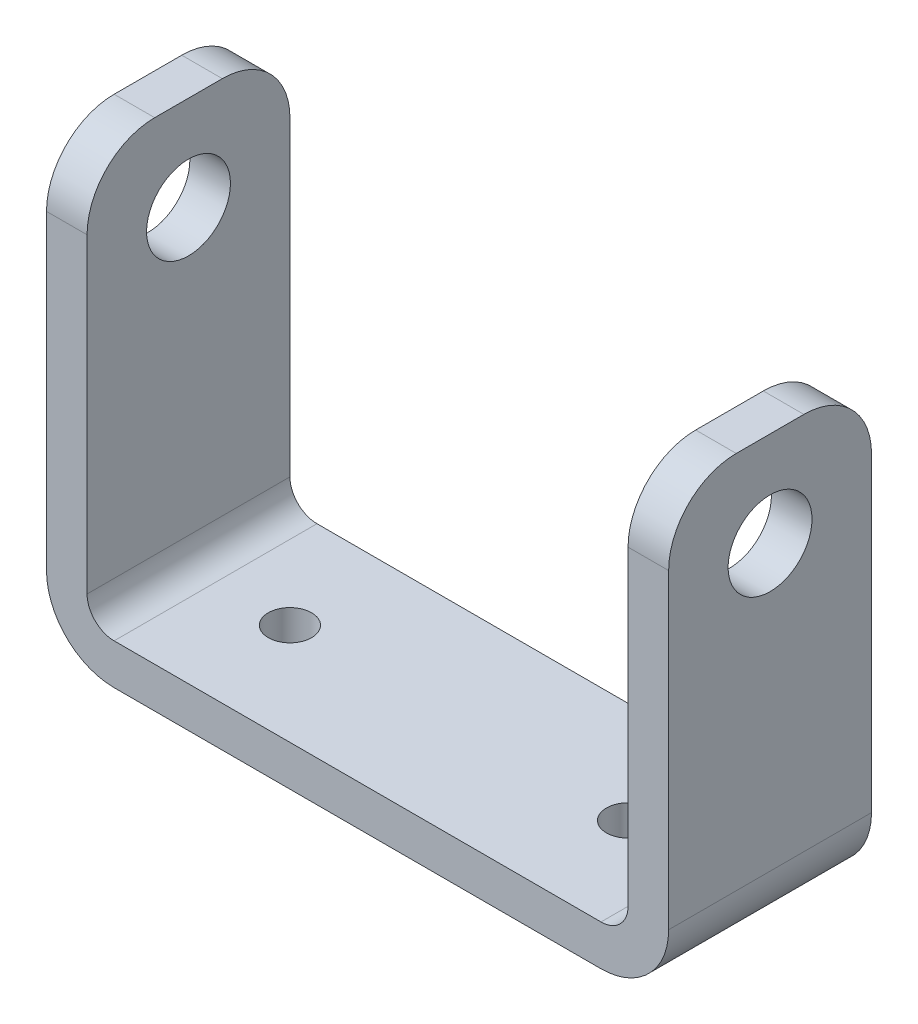
SolidWorks part; units mm, degrees
ref_plane "正面" through (0, 0, 0) normal (0, 0, 1) x (1, 0, 0)
ref_plane "平面" through (0, 0, 0) normal (0, 1, 0) x (1, 0, 0)
ref_plane "右側面" through (0, 0, 0) normal (1, 0, 0) x (0, 0, -1)
sketch "ｽｹｯﾁ1" plane through (0, 0, 0) normal (0, 0, 1) x (1, 0, 0)
  line L0 (0, 0) -> (0, -30)
  line L1 (0, -30) -> (40, -30)
  line L2 (40, -30) -> (40, 0)
  line L3 (-3, 0) -> (-3, -33)
  line L4 (-3, -33) -> (43, -33)
  line L5 (43, -33) -> (43, 0)
  line L6 (0, 0) -> (-3, 0)
  line L7 (40, 0) -> (43, 0)
  line L8 (40, 0) -> (10, -30) construction
  dimension "D1" = 3
  dimension "D2" = 30
  dimension "D3" = 40
  dimension "D4" = 45
extrude "ﾎﾞｽ - 押し出し1" add sketch "ｽｹｯﾁ1" along normal blind 15
sketch "ｽｹｯﾁ2" plane through (43, 0, 0) normal (1, 0, 0) x (0, 0, -1)
  line L0 (-7.5, 0) -> (-7.5, -7) construction
  line L1 (-15, 0) -> (0, 0) construction
  circle A0 centre (-7.5, -7) radius 3.1
  dimension "D1" = 7
  dimension "D2" = 6.2
extrude "ｶｯﾄ - 押し出し1" cut sketch "ｽｹｯﾁ2" against normal through all
fillet "ﾌｨﾚｯﾄ1" radius 5 4 edges at (-1.5, 0, 0) (-1.5, 0, 15) (41.5, 0, 0) (41.5, 0, 15)
sketch "ｽｹｯﾁ3" plane through (0, -30, 0) normal (0, 1, 0) x (1, 0, 0)
  line L0 (20, 0) -> (20, -15) construction
  line L1 (40, 0) -> (0, 0) construction
  line L2 (40, -15) -> (0, -15) construction
  line L3 (32.5, -7.5) -> (7.5, -7.5) construction
  circle A0 centre (7.5, -7.5) radius 1.6
  circle A1 centre (32.5, -7.5) radius 1.6
  circle A2 centre (32.5, -7.5) radius 3 construction
  point P9 (20, -7.5)
  dimension "D1" = 3.2
  dimension "D3" = 6
  dimension "D2" = 25
extrude "ｶｯﾄ - 押し出し2" cut sketch "ｽｹｯﾁ3" against normal through all
fillet "ﾌｨﾚｯﾄ3" radius 2 2 edges at (40, -30, 7.5) (0, -30, 7.5)
fillet "ﾌｨﾚｯﾄ4" radius 5 2 edges at (43, -33, 7.5) (-3, -33, 7.5)
